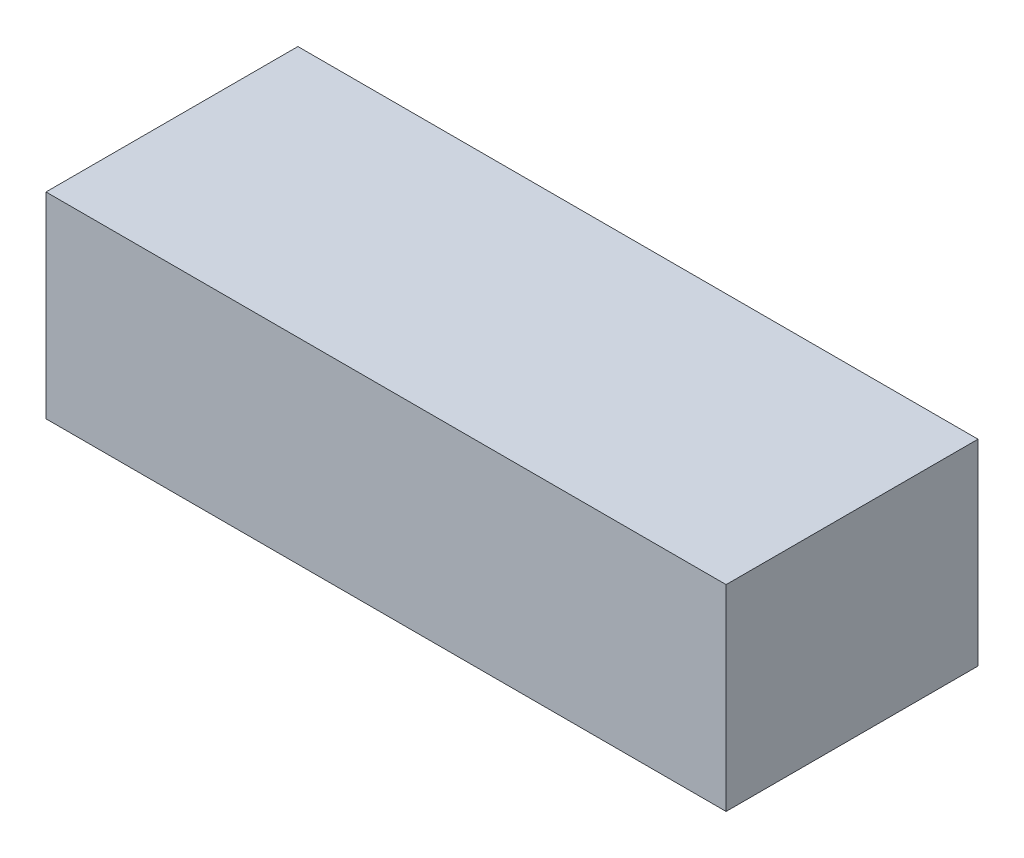
SolidWorks part; units mm, degrees
ref_plane "前视基准面" through (0, 0, 0) normal (0, 0, 1) x (1, 0, 0)
ref_plane "上视基准面" through (0, 0, 0) normal (0, 1, 0) x (1, 0, 0)
ref_plane "右视基准面" through (0, 0, 0) normal (1, 0, 0) x (0, 0, -1)
other "Configuration Table"
sketch "草图1" plane through (0, 0, 0) normal (1, 0, 0) x (0, 0, -1)
  line L1 (-25, -19.5) -> (25, -19.5)
  line L2 (-25, -19.5) -> (-25, 19.5)
  line L3 (-25, 19.5) -> (25, 19.5)
  line L4 (25, -19.5) -> (25, 19.5)
  line L5 (-25, -19.5) -> (25, 19.5) construction
  line L6 (-25, 19.5) -> (25, -19.5) construction
  point P0 (0, 0)
  dimension "D1" = 50
  dimension "D2" = 39
extrude "凸台-拉伸1" add sketch "草图1" along normal blind 135
